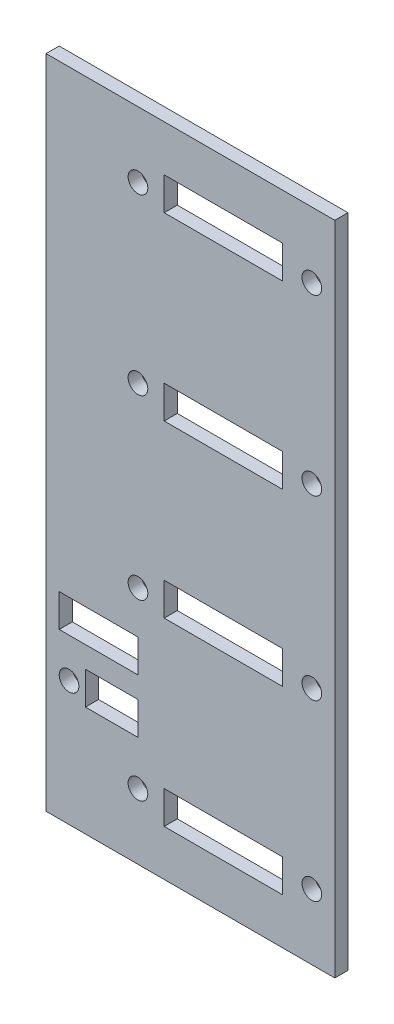
SolidWorks part; units mm, degrees
ref_plane "Front Plane" through (0, 0, 0) normal (0, 0, 1) x (1, 0, 0)
ref_plane "Top Plane" through (0, 0, 0) normal (0, 1, 0) x (1, 0, 0)
ref_plane "Right Plane" through (0, 0, 0) normal (1, 0, 0) x (0, 0, -1)
sketch "Sketch1" plane through (0, 0, 0) normal (0, 0, 1) x (1, 0, 0)
  line L1 (22, -50) -> (-22, -50)
  line L2 (22, -50) -> (22, 50)
  line L3 (22, 50) -> (-22, 50)
  line L4 (-22, -50) -> (-22, 50)
  line L5 (22, -50) -> (-22, 50) construction
  line L6 (22, 50) -> (-22, -50) construction
  point P0 (0, 0)
  dimension "D1" = 44
  dimension "D2" = 100
extrude "Boss-Extrude1" add sketch "Sketch1" along normal blind 2
sketch "Sketch2" plane through (0, 0, 2) normal (0, 0, 1) x (1, 0, 0)
  line L0 (-22, -50) -> (22, -50) construction
  line L1 (0, 0) -> (0, -50) construction
  line L2 (-22, 50) -> (-22, -50) construction
  line L5 (0, 0) -> (-22, 0) construction
  circle A0 centre (-8, -40) radius 1.5
  circle A1 centre (18.5, -40) radius 1.5
  circle A2 centre (18.5, -13.5) radius 1.5
  circle A3 centre (-8, -13.5) radius 1.5
  circle A4 centre (18.5, 40) radius 1.5
  circle A5 centre (-8, 40) radius 1.5
  circle A6 centre (18.5, 13.5) radius 1.5
  circle A7 centre (-8, 13.5) radius 1.5
  dimension "D1" = 3
  dimension "D2" = 10
  dimension "D3" = 3
  dimension "D6" = 10
  dimension "D7" = 26.5
  dimension "D10" = 14
  dimension "D11" = 3
  dimension "D12" = 3
  dimension "D4" = 26.5
  dimension "D5" = 18.5
  dimension "D8" = 26.5
  dimension "D9" = 26.5
extrude "Cut-Extrude1" cut sketch "Sketch2" against normal blind 2
sketch "Sketch3" plane through (0, 0, 2) normal (0, 0, 1) x (1, 0, 0)
  line L0 (22, 50) -> (-22, 50) construction
  line L1 (-4, 43) -> (14, 43)
  line L2 (-4, 43) -> (-4, 38)
  line L3 (-4, 38) -> (14, 38)
  line L4 (14, 43) -> (14, 38)
  line L5 (-4, 43) -> (14, 38) construction
  line L6 (-4, 38) -> (14, 43) construction
  line L7 (-22, 50) -> (-22, -50) construction
  line L8 (-22, 26.7524) -> (22, 26.7524) construction
  line L10 (22, -50) -> (22, 50) construction
  line L11 (14, 10.5047) -> (14, 15.5047)
  line L12 (-4, 10.5047) -> (14, 10.5047)
  line L13 (-4, 10.5047) -> (-4, 15.5047)
  line L14 (-4, 15.5047) -> (14, 15.5047)
  line L15 (-22, 0) -> (22, 0) construction
  line L16 (-4, -15.5047) -> (14, -15.5047)
  line L17 (-4, -10.5047) -> (-4, -15.5047)
  line L18 (-4, -10.5047) -> (14, -10.5047)
  line L19 (14, -10.5047) -> (14, -15.5047)
  line L20 (14, -43) -> (14, -38)
  line L21 (-4, -43) -> (-4, -38)
  line L22 (-4, -43) -> (14, -43)
  line L23 (-4, -38) -> (14, -38)
  point P0 (5, 40.5)
  dimension "D1" = 18
  dimension "D2" = 7
  dimension "D3" = 5
  dimension "D4" = 18
extrude "Cut-Extrude2" cut sketch "Sketch3" against normal blind 10
sketch "Sketch4" plane through (0, 0, 2) normal (0, 0, 1) x (1, 0, 0)
  line L0 (-22, -50) -> (22, -50) construction
  line L1 (-22, 50) -> (-22, -50) construction
  line L3 (-20, -25) -> (-8, -25)
  line L4 (-20, -25) -> (-20, -20)
  line L5 (-20, -20) -> (-8, -20)
  line L6 (-8, -25) -> (-8, -20)
  line L7 (-20, -25) -> (-8, -20) construction
  line L8 (-20, -20) -> (-8, -25) construction
  line L9 (-16, -33.2461) -> (-8, -33.2461)
  line L10 (-16, -33.2461) -> (-16, -28.2461)
  line L11 (-16, -28.2461) -> (-8, -28.2461)
  line L12 (-8, -33.2461) -> (-8, -28.2461)
  line L13 (-16, -33.2461) -> (-8, -28.2461) construction
  line L14 (-16, -28.2461) -> (-8, -33.2461) construction
  circle A0 centre (-18.5, -31) radius 1.5
  point P6 (-14, -22.5)
  point P11 (-12, -30.7461)
  dimension "D2" = 3
  dimension "D1" = 19
  dimension "D3" = 3.5
  dimension "D4" = 5
  dimension "D5" = 12
  dimension "D6" = 6
  dimension "D7" = 2
  dimension "D8" = 8
  dimension "D9" = 5
  dimension "D10" = 6
  dimension "D11" = 16.7539
extrude "Cut-Extrude3" cut sketch "Sketch4" against normal through all
